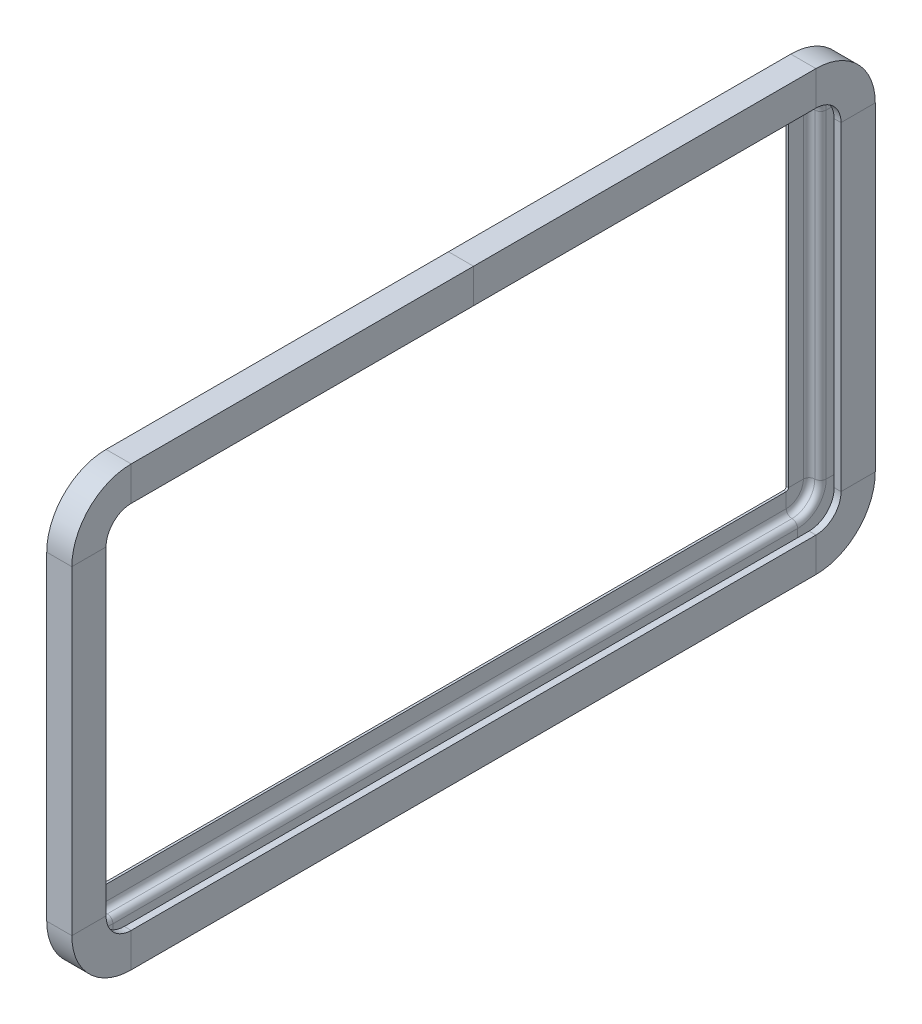
SolidWorks part; units mm, degrees
material "Силикон"
ref_plane "Front Plane" through (0, 0, 0) normal (0, 0, 1) x (1, 0, 0)
ref_plane "Top Plane" through (0, 0, 0) normal (0, 1, 0) x (1, 0, 0)
ref_plane "Right Plane" through (0, 0, 0) normal (1, 0, 0) x (0, 0, -1)
sketch "Sketch1" plane through (0, 0, 0) normal (0, 0, 1) x (1, 0, 0)
  line L0 (5, 70) -> (5, 89.5) construction
  line L1 (5, 81) -> (5, 89.5)
  line L2 (0, 89.5) -> (0, 70) construction
  line L3 (0, 89.5) -> (0, 82.5)
  line L8 (2.5, 97.3645) -> (2.5, 64.2965) construction
  line L9 (-3, 81) -> (-3, 96)
  line L10 (-3, 96) -> (8, 96)
  line L11 (8, 96) -> (8, 81)
  line L15 (5, 81) -> (8, 81)
  line L21 (-6, 81) -> (-3, 81)
  line L23 (-5, 77.5) -> (-5, 70) construction
  line L24 (-5, 77.5) -> (-5, 71)
  line L25 (-6, 71) -> (-5, 71)
  line L26 (-6, 81) -> (-6, 71)
  arc A0 (5, 89.5) -> (2.5, 92) centre (2.5, 89.5) ccw construction
  arc A1 (5, 89.5) -> (2.5, 92) centre (2.5, 89.5) ccw
  arc A2 (2.5, 92) -> (0, 89.5) centre (2.5, 89.5) ccw construction
  arc A3 (2.5, 92) -> (0, 89.5) centre (2.5, 89.5) ccw
  arc A4 (-2.5, 80) -> (0, 82.5) centre (-2.5, 82.5) ccw construction
  arc A5 (-2.5, 80) -> (0, 82.5) centre (-2.5, 82.5) ccw
  arc A6 (-2.5, 80) -> (-5, 77.5) centre (-2.5, 77.5) ccw construction
  arc A8 (-2.5, 80) -> (-5, 77.5) centre (-2.5, 77.5) ccw construction
  arc A9 (-2.5, 80) -> (-5, 77.5) centre (-2.5, 77.5) ccw
  point P25 (-5, 77.5)
  dimension "D1" = 3
  dimension "D2" = 4
  dimension "D3" = 3
  dimension "D4" = 15
  dimension "D5" = 1
  dimension "D6" = 10
  dimension "D7" = 1
ref_plane "Plane4" through (2.5, 0, 0) normal (1, 0, 0) x (0, 0, -1)
sketch "Sketch2" plane through (2.5, 0, 0) normal (1, 0, 0) x (0, 0, -1)
  line L1 (150, 92) -> (-150, 92) construction
  line L2 (150, 92) -> (-150, 92)
  line L3 (-172, 70) -> (-172, -70) construction
  line L4 (-172, 70) -> (-172, -70)
  line L5 (-150, -92) -> (150, -92) construction
  line L6 (-150, -92) -> (150, -92)
  line L7 (172, -70) -> (172, 70) construction
  line L8 (172, -70) -> (172, 70)
  arc A0 (-150, 92) -> (-172, 70) centre (-150, 70) ccw construction
  arc A1 (-150, 92) -> (-172, 70) centre (-150, 70) ccw
  arc A2 (172, 70) -> (150, 92) centre (150, 70) ccw construction
  arc A3 (172, 70) -> (150, 92) centre (150, 70) ccw
  arc A4 (-172, -70) -> (-150, -92) centre (-150, -70) ccw construction
  arc A5 (-172, -70) -> (-150, -92) centre (-150, -70) ccw
  arc A6 (150, -92) -> (172, -70) centre (150, -70) ccw construction
  arc A7 (150, -92) -> (172, -70) centre (150, -70) ccw
sweep "Sweep1" add profiles "Sketch1" path "Sketch2"
